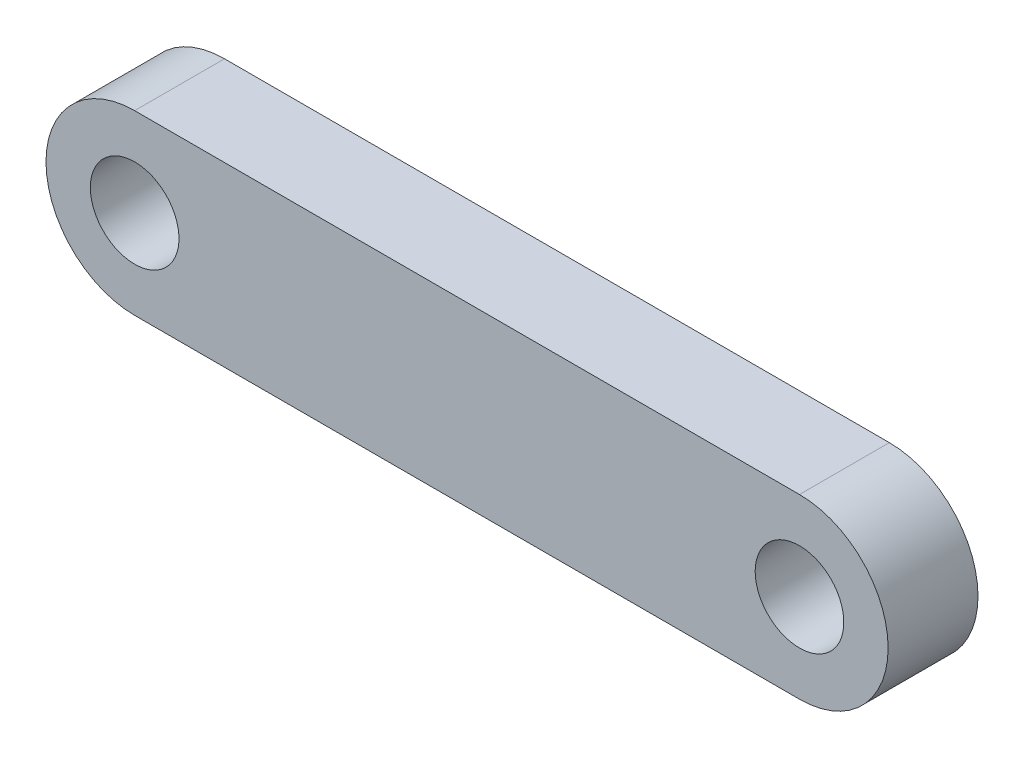
SolidWorks part; units mm, degrees
ref_plane "Front Plane" through (0, 0, 0) normal (0, 0, 1) x (1, 0, 0)
ref_plane "Top Plane" through (0, 0, 0) normal (0, 1, 0) x (1, 0, 0)
ref_plane "Right Plane" through (0, 0, 0) normal (1, 0, 0) x (0, 0, -1)
sketch "Sketch1" plane through (0, 0, 0) normal (0, 0, 1) x (1, 0, 0)
  line L0 (-9.525, 0) -> (9.525, 0) construction
  line L1 (-9.525, 2.54) -> (9.525, 2.54)
  line L2 (-9.525, -2.54) -> (9.525, -2.54)
  arc A0 (-9.525, 2.54) -> (-9.525, -2.54) centre (-9.525, 0) ccw
  arc A1 (9.525, -2.54) -> (9.525, 2.54) centre (9.525, 0) ccw
  circle A2 centre (-9.525, 0) radius 1.27
  circle A3 centre (9.525, 0) radius 1.27
  point P2 (0, 0)
  dimension "D2" = 2.54
  dimension "D3" = 2.54
  dimension "D1" = 19.05
extrude "Boss-Extrude1" add sketch "Sketch1" along normal blind 2.575
